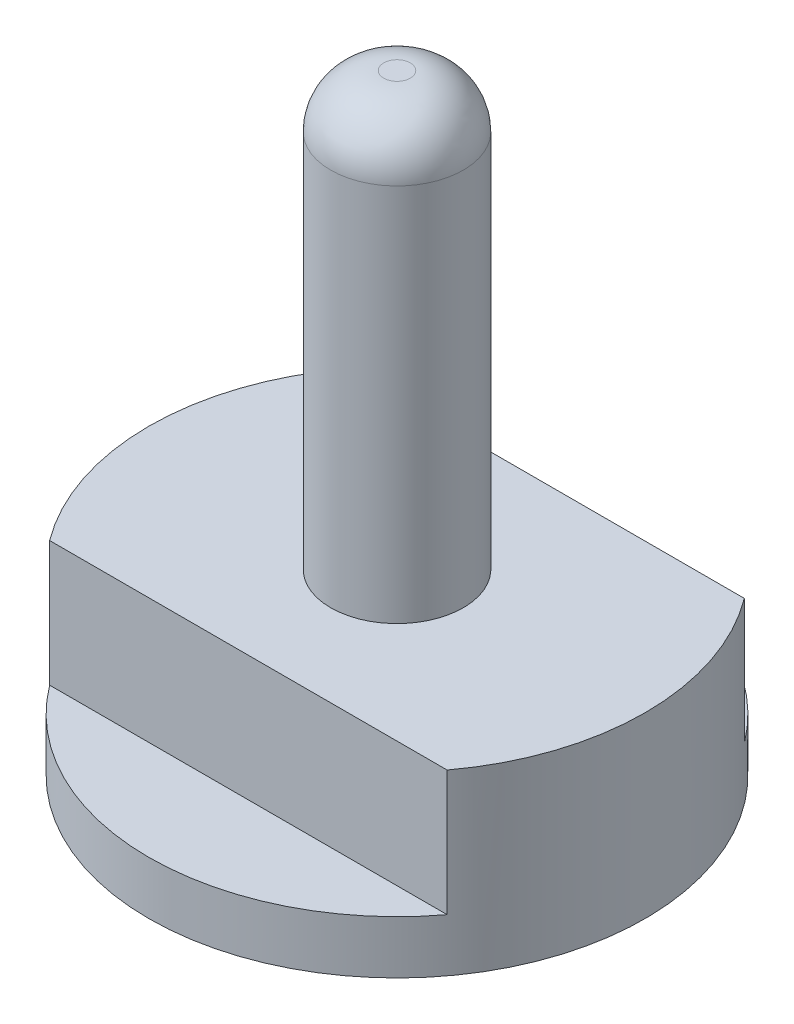
SolidWorks part; units mm, degrees
ref_plane "Plane1" through (0, 0, 0) normal (0, 0, 1) x (1, 0, 0)
ref_plane "Plane2" through (0, 0, 0) normal (0, 1, 0) x (1, 0, 0)
ref_plane "Plane3" through (0, 0, 0) normal (1, 0, 0) x (0, 0, -1)
sketch "Sketch2" plane through (0, 3.36, 0) normal (0, 1, 0) x (-1, 0, 0)
  line L0 (-3.7437, 0) -> (3.7437, 0) construction
  line L1 (-3.7437, 5.6) -> (3.7437, 5.6) construction
  line L2 (-3.7437, 0) -> (3.7437, 0)
  line L3 (-3.7437, 5.6) -> (3.7437, 5.6)
  arc A0 (3.7437, 0) -> (3.7437, 5.6) centre (0, 2.8) ccw construction
  arc A1 (-3.7437, 5.6) -> (-3.7437, 0) centre (0, 2.8) ccw construction
  arc A2 (3.7437, 0) -> (3.7437, 5.6) centre (0, 2.8) ccw
  arc A3 (-3.7437, 5.6) -> (-3.7437, 0) centre (0, 2.8) ccw
extrude "Base-Extrude" add sketch "Sketch2" against normal up to surface (3.36 mm away)
sketch "Sketch3" plane through (0, 3.36, 0) normal (0, 1, 0) x (-1, 0, 0)
  circle A0 centre (0, 2.8) radius 1.25
  arc A1 (3.7437, 0) -> (3.7437, 5.6) centre (0, 2.8) ccw construction
  dimension "D1" = 2.5
extrude "Boss-Extrude1" add sketch "Sketch3" along normal blind 8.14
fillet "Fillet1" radius 1 1 edges at (0, 11.5, 4.05)
sketch "Sketch4" plane through (0, 0, 0) normal (0, -1, 0) x (1, 0, 0)
  circle A0 centre (0, 2.8) radius 4.675
  arc A1 (3.7437, 0) -> (3.7437, 5.6) centre (0, 2.8) ccw construction
extrude "Boss-Extrude2" add sketch "Sketch4" against normal blind 1
sketch "Sketch5" plane through (0, 0, 0) normal (0, -1, 0) x (1, 0, 0)
  circle A1 centre (0, 2.8) radius 1.675
  circle A2 centre (0, 2.8) radius 1.675
  circle A3 centre (0, 2.8) radius 1.175
  circle A4 centre (0, 2.8) radius 1.175
  dimension "D1" = 3
  dimension "D2" = 3.5
extrude "Boss-Extrude3" add sketch "Sketch5" along normal blind 2
